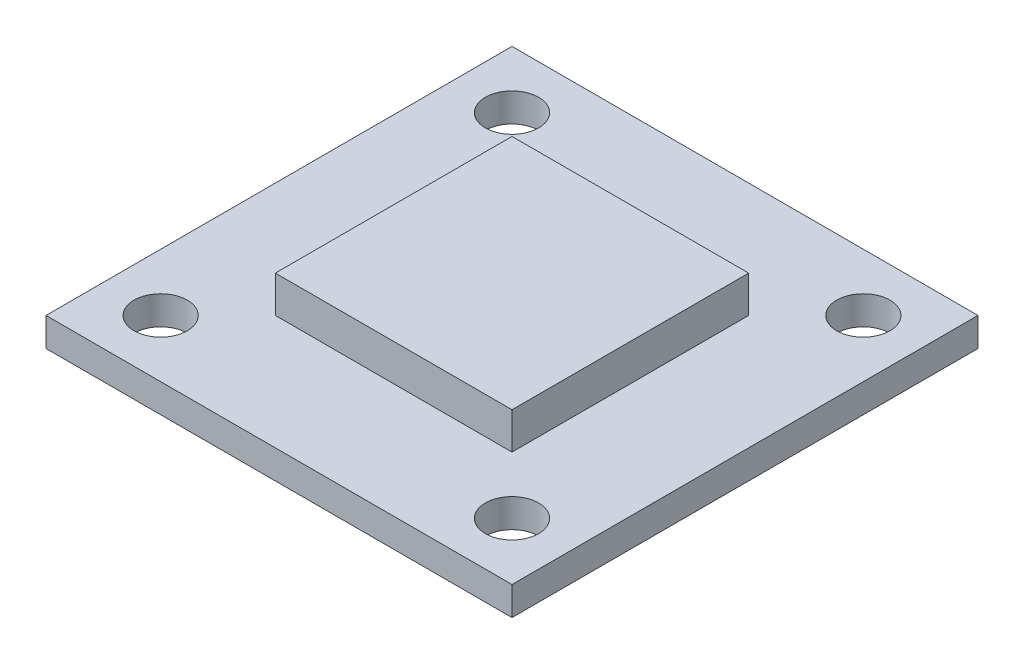
SolidWorks part; units mm, degrees
ref_plane "Front Plane" through (0, 0, 0) normal (0, 0, 1) x (1, 0, 0)
ref_plane "Top Plane" through (0, 0, 0) normal (0, 1, 0) x (1, 0, 0)
ref_plane "Right Plane" through (0, 0, 0) normal (1, 0, 0) x (0, 0, -1)
sketch "Sketch1" plane through (0, 0, 0) normal (0, 1, 0) x (1, 0, 0)
  line L1 (-12.9032, -12.9032) -> (12.9032, -12.9032)
  line L2 (-12.9032, -12.9032) -> (-12.9032, 12.9032)
  line L3 (-12.9032, 12.9032) -> (12.9032, 12.9032)
  line L4 (12.9032, -12.9032) -> (12.9032, 12.9032)
  line L5 (-12.9032, -12.9032) -> (12.9032, 12.9032) construction
  line L6 (-12.9032, 12.9032) -> (12.9032, -12.9032) construction
  point P0 (0, 0)
  dimension "D1" = 25.8064
  dimension "D2" = 25.8064
extrude "Boss-Extrude1" add sketch "Sketch1" along normal blind 1.5875
sketch "Sketch2" plane through (0, 1.5875, 0) normal (0, 1, 0) x (1, 0, 0)
  line L1 (-6.5532, -6.5532) -> (6.5532, -6.5532)
  line L2 (-6.5532, -6.5532) -> (-6.5532, 6.5532)
  line L3 (-6.5532, 6.5532) -> (6.5532, 6.5532)
  line L4 (6.5532, -6.5532) -> (6.5532, 6.5532)
  line L5 (-6.5532, -6.5532) -> (6.5532, 6.5532) construction
  line L6 (-6.5532, 6.5532) -> (6.5532, -6.5532) construction
  point P0 (0, 0)
  dimension "D1" = 13.1064
  dimension "D2" = 13.1064
extrude "Boss-Extrude2" add sketch "Sketch2" along normal blind 2.032
sketch "Sketch3" plane through (0, 1.5875, 0) normal (0, 1, 0) x (1, 0, 0)
  line L5 (-9.7282, -9.7282) -> (9.7282, 9.7282) construction
  line L6 (-9.7282, 9.7282) -> (9.7282, -9.7282) construction
  point P0 (0, 0)
  point P7 (-9.7282, 9.7282)
  point P8 (9.7282, 9.7282)
  point P9 (9.7282, -9.7282)
  point P10 (-9.7282, -9.7282)
  dimension "D1" = 19.4564
  dimension "D2" = 19.4564
hole_wizard "#32 (0.116) Diameter Hole1" positions "3DSketch1" profile "Sketch4" hole size "#32" standard "ANSI Inch" end condition through all
sketch3d "3DSketch1"
  point P0 (-9.7282, 1.5875, -9.7282)
  point P3 (-9.7282, 1.5875, 9.7282)
  point P6 (9.7282, 1.5875, 9.7282)
  point P9 (9.7282, 1.5875, -9.7282)
sketch "Sketch4" plane through (-9.7282, 1.5875, -9.7282) normal (1, 0, 0) x (0, 0, 1)
  line L0 (0, 0) -> (0, 1.5875)
  line L1 (0, 1.5875) -> (1.4732, 1.5875)
  line L2 (1.4732, 1.5875) -> (1.4732, 0)
  line L5 (1.4732, 0) -> (0, 0)
  line L11 (0, -6.35) -> (0, 107.95) construction
  dimension "Thru Hole Dia." = 2.9464
  dimension "Thru Hole Depth" = 1.5875
